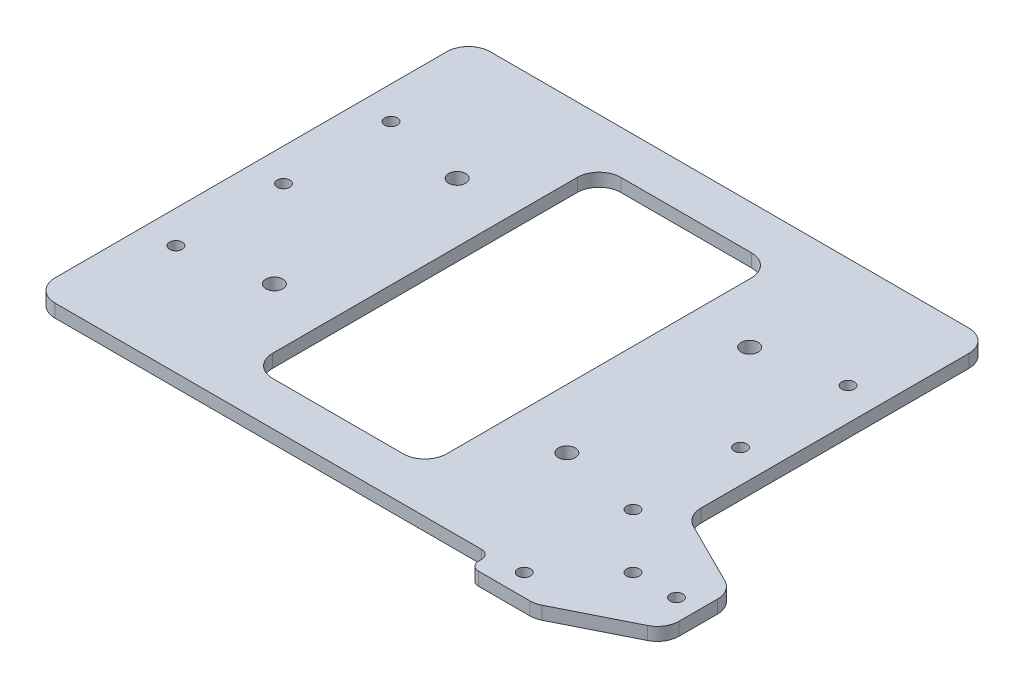
SolidWorks part; units mm, degrees
material "Thornel Mat VMA"
ref_plane "前视基准面" through (0, 0, 0) normal (0, 0, 1) x (1, 0, 0)
ref_plane "上视基准面" through (0, 0, 0) normal (0, 1, 0) x (1, 0, 0)
ref_plane "右视基准面" through (0, 0, 0) normal (1, 0, 0) x (0, 0, -1)
other "Configuration Table"
sketch "草图1" plane through (0, 0, 0) normal (0, 1, 0) x (1, 0, 0)
  line L0 (-57.7913, 0) -> (59.9834, 0) construction
  line L1 (-60, -50) -> (60, -50) construction
  line L2 (-60, -50) -> (-60, 50)
  line L3 (-60, 50) -> (60, 50)
  line L4 (60, -50) -> (60, 50) construction
  line L5 (-60, -50) -> (60, 50) construction
  line L6 (-60, 50) -> (60, -50) construction
  line L7 (-20, -40) -> (20, -40)
  line L8 (-20, -40) -> (-20, 40)
  line L9 (-20, 40) -> (20, 40)
  line L10 (20, -40) -> (20, 40)
  line L11 (-20, -40) -> (20, 40) construction
  line L12 (-20, 40) -> (20, -40) construction
  line L13 (0, 61.4014) -> (0, -57.8366) construction
  line L14 (-69.1159, -37.2) -> (93.1137, -37.2) construction
  line L15 (52.5, 61.4014) -> (52.5, -102.4683) construction
  line L16 (-60, -50) -> (45, -50)
  line L17 (45, -50) -> (45, -54.7)
  line L18 (45, -54.7) -> (60, -54.7)
  line L19 (60, -54.7) -> (80, -44.7)
  line L20 (80, -44.7) -> (80, -29.7)
  line L21 (80, -29.7) -> (60, -19.7)
  line L22 (60, -19.7) -> (60, 50)
  circle A0 centre (-33.6, 21) radius 1.95
  circle A1 centre (-33.6, -21) radius 1.95
  circle A2 centre (33.6, -21) radius 1.95
  circle A3 centre (33.6, 21) radius 1.95
  circle A4 centre (65, -37.2) radius 1.45
  circle A5 centre (75, -37.2) radius 1.45
  circle A6 centre (52.5, -24.7) radius 1.45
  circle A7 centre (52.5, -49.7) radius 1.45
  circle A8 centre (52.5, 0) radius 1.45
  circle A9 centre (-52.5, 0) radius 1.45
  circle A10 centre (-52.5, -24.7) radius 1.45
  circle A11 centre (-52.5, 24.7) radius 1.45
  circle A12 centre (52.5, 24.7) radius 1.45
  point P0 (0, 0)
  point P6 (0, 0)
  point P45 (51.3045, 0)
  dimension "D5" = 3.9
  dimension "D6" = 42
  dimension "D7" = 67.2
  dimension "D13" = 10
  dimension "D14" = 2.9
  dimension "D15" = 5
  dimension "D16" = 5
  dimension "D17" = 5
  dimension "D1" = 120
  dimension "D2" = 80
  dimension "D3" = 100
  dimension "D4" = 40
  dimension "D8" = 12.8
  dimension "D9" = 7.5
  dimension "D10" = 12.5
  dimension "D11" = 12.5
  dimension "D12" = 5
  dimension "D18" = 7.5
  dimension "D19" = 7.5
  dimension "D20" = 15
extrude "凸台-拉伸1" add sketch "草图1" along normal blind 3
fillet "圆角1" radius 5 11 edges at (-20, 1.5, 40) (20, 1.5, 40) (-60, 1.5, -50) (20, 1.5, -40) (-20, 1.5, -40) (60, 1.5, 19.7) (80, 1.5, 29.7) (60, 1.5, 54.7) (-60, 1.5, 50) (60, 1.5, -50) (80, 1.5, 44.7)
fillet "圆角3" radius 2 2 edges at (45, 1.5, 54.7) (45, 1.5, 50)
